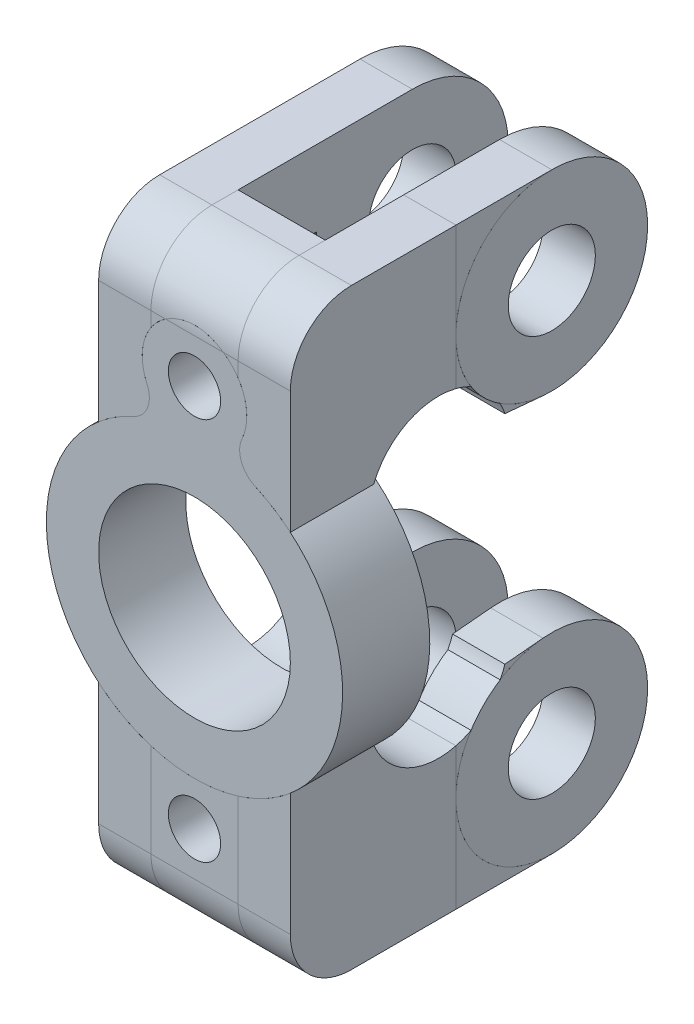
SolidWorks part; units mm, degrees
ref_plane "Front" through (0, 0, 0) normal (0, 0, 1) x (1, 0, 0)
ref_plane "Top" through (0, 0, 0) normal (0, 1, 0) x (1, 0, 0)
ref_plane "Right" through (0, 0, 0) normal (1, 0, 0) x (0, 0, -1)
sketch "Эскиз1" plane through (0, 0, 0) normal (0, 0, 1) x (1, 0, 0)
  line L0 (0, 0) -> (0, 11) construction
  circle A0 centre (0, 0) radius 5.5
  circle A1 centre (0, 0) radius 8.5
  circle A2 centre (0, 11) radius 1.5
  circle A3 centre (0, 11) radius 3
  circle A4 centre (-4.0908, 9.125) radius 1.5
  circle A5 centre (4.0908, 9.125) radius 1.5
  dimension "D1" = 3
  dimension "D2" = 6
  dimension "D3" = 11
  dimension "D4" = 17
  dimension "D5" = 3
  dimension "D6" = 11
extrude "Бобышка-Вытянуть1" add sketch "Эскиз1" along normal blind 5
sketch "Эскиз2" plane through (0, 0, 0) normal (1, 0, 0) x (0, 0, -1)
  line L0 (0, 0) -> (30.7482, 0) construction
  circle A0 centre (10, 11.5) radius 5.5
  circle A1 centre (10, -11.5) radius 5.5
  circle A2 centre (10, 11.5) radius 2.5
  circle A3 centre (10, -11.5) radius 2.5
  dimension "D1" = 11
  dimension "D4" = 5
  dimension "D2" = 10
  dimension "D3" = 23
extrude "Бобышка-Вытянуть2" add sketch "Эскиз2" against normal blind 3 from offset 2.5 separate body offset against normal yes
sketch "Эскиз3" plane through (0, 0, 0) normal (1, 0, 0) x (0, 0, -1)
  line L0 (0, 0) -> (30.7482, 0) construction
  circle A0 centre (10, 11.5) radius 5.5
  circle A1 centre (10, -11.5) radius 5.5
  circle A2 centre (10, 11.5) radius 2.5
  circle A3 centre (10, -11.5) radius 2.5
  circle A4 centre (10, 11.5) radius 5.5 construction
  circle A5 centre (10, -11.5) radius 5.5 construction
extrude "Бобышка-Вытянуть3" add sketch "Эскиз3" along normal blind 3 from offset 2.5 separate body
sketch "Эскиз4" plane through (0, 0, 5) normal (0, 0, 1) x (1, 0, 0)
  line L0 (-5.5, -6.4807) -> (-5.5, -17)
  line L1 (-5.5, -17) -> (-2.5, -17)
  line L2 (-2.5, -17) -> (-2.5, -8.124)
  line L3 (-2.5, -17) -> (-2.5, -6) construction
  line L4 (-5.5, -17) -> (-2.5, -17) construction
  line L5 (-5.5, -6) -> (-5.5, -17) construction
  line L6 (2.5, -8.124) -> (2.5, -17)
  line L7 (2.5, -17) -> (5.5, -17)
  line L8 (5.5, -17) -> (5.5, -6.4807)
  line L9 (-5.5, 6.4807) -> (-5.5, 17)
  line L10 (-5.5, 17) -> (-2.5, 17)
  line L11 (-2.5, 17) -> (-2.5, 12.6583)
  line L12 (-2.5, 6) -> (-2.5, 17) construction
  line L13 (-2.5, 17) -> (-5.5, 17) construction
  line L14 (-5.5, 17) -> (-5.5, 6) construction
  line L15 (5.5, 6.4807) -> (5.5, 17)
  line L16 (5.5, 17) -> (2.5, 17)
  line L17 (2.5, 17) -> (2.5, 12.6583)
  line L18 (2.5, -17) -> (5.5, -17) construction
  line L19 (5.5, -17) -> (5.5, -6) construction
  line L20 (2.5, -6) -> (2.5, -17) construction
  line L21 (5.5, 6) -> (5.5, 17) construction
  line L22 (5.5, 17) -> (2.5, 17) construction
  line L23 (2.5, 17) -> (2.5, 6) construction
  circle A0 centre (0, 0) radius 8.5
  arc A1 (2.7272, 9.75) -> (-2.7272, 9.75) centre (0, 11) ccw construction
  circle A2 centre (0, 11) radius 3
  arc A3 (-3.4772, 7.7563) -> (3.4772, 7.7563) centre (0, 0) ccw construction
  arc M13 (-2.7272, 9.75) -> (-3.4772, 7.7563) centre (-4.0908, 9.125) cw
  arc M14 (-3.4772, 7.7563) -> (3.4772, 7.7563) centre (0, 0) ccw
  arc M15 (3.4772, 7.7563) -> (2.7272, 9.75) centre (4.0908, 9.125) cw
  arc M16 (2.7272, 9.75) -> (-2.7272, 9.75) centre (0, 11) ccw
  dimension "D1" = 17
  dimension "D2" = 6
extrude "Бобышка-Вытянуть4" add sketch "Эскиз4" against normal blind 9.5 separate body contours L1 L2 L0 M14 | L7 L8 L6 M14 | L16 L17 L15 M16 M15 M14 | L11 L10 L9 M14 M13 M16
sketch "Эскиз5" plane through (-5.5, 0, 0) normal (-1, 0, 0) x (0, 0, 1)
  line L0 (-10, 17) -> (-4.5, 17)
  line L1 (-4.5, 17) -> (-4.5, 6.4807)
  line L2 (-4.5, 6.4807) -> (-9.4983, 6.0229)
  line L3 (-9.4983, -6.0229) -> (-4.5, -6.4807)
  line L4 (-4.5, -6.4807) -> (-4.5, -17)
  line L5 (-4.5, -17) -> (-10, -17)
  circle A0 centre (-10, 11.5) radius 5.5 construction
  circle A1 centre (-10, 11.5) radius 5.5
  circle A2 centre (-10, -11.5) radius 5.5 construction
  circle A3 centre (-10, -11.5) radius 5.5
  circle M4 centre (-10, 11.5) radius 5.5
extrude "Бобышка-Вытянуть5" add sketch "Эскиз5" against normal up to surface (3 mm away) contours A3 L4 L3 | A3 L5 L4 | L2 L1 M4 | L1 L0 M4 up to face at (-2.5, 11.5, -12.5)
sketch "Эскиз6" plane through (5.5, 0, 0) normal (1, 0, 0) x (0, 0, -1)
  line L0 (10, 17) -> (4.5, 17)
  line L1 (10, 17) -> (-5, 17) construction
  line L2 (4.5, 17) -> (4.5, 6.4807)
  line L3 (4.5, 6.4807) -> (9.4983, 6.0229)
  line L4 (10, -17) -> (4.5, -17)
  line L5 (4.5, -17) -> (4.5, -6.4807)
  line L6 (4.5, -6.4807) -> (9.4983, -6.0229)
  line L7 (10, -17) -> (-5, -17) construction
  circle A0 centre (10, 11.5) radius 5.5
  circle A1 centre (10, -11.5) radius 5.5
  circle M4 centre (10, 11.5) radius 5.5
  dimension "D1" = 11
  dimension "D2" = 11
extrude "Бобышка-Вытянуть6" add sketch "Эскиз6" against normal up to surface (3 mm away) separate body contours A1 L6 L5 | A1 L5 L4 | L0 L2 M4 | L2 L3 M4 up to face at (2.5, 11.5, -15.5)
sketch "Эскиз7" plane through (0, 0, 5) normal (0, 0, 1) x (1, 0, 0)
  line L0 (-2.5, -8.124) -> (-2.5, -17)
  line L1 (-2.5, -17) -> (2.5, -17)
  line L2 (2.5, -17) -> (2.5, -8.124)
  line L3 (-2.5, 12.6583) -> (-2.5, 17)
  line L4 (-2.5, 17) -> (2.5, 17)
  line L5 (2.5, 17) -> (2.5, 12.6583)
  line L6 (2.5, 17) -> (2.5, 12.6583) construction
  circle A0 centre (0, 0) radius 8.5
  circle A1 centre (0, 11) radius 3
  line M4 (2.5, -8.124) -> (2.5, -17)
  dimension "D1" = 17
  dimension "D2" = 6
extrude "Бобышка-Вытянуть7" add sketch "Эскиз7" against normal blind 5 separate body contours A1 L5 L4 L3 | A0 L0 L1 M4
sketch "Эскиз8" plane through (5.5, 0, 0) normal (1, 0, 0) x (0, 0, -1)
  line L0 (0, 0) -> (22.4841, 0) construction
  line L2 (0, -8.5) -> (0, 7.7563) construction
  circle A0 centre (3.5, 5) radius 4
  circle A1 centre (3.5, -5) radius 4
  point P9 (0, 4.2751)
  dimension "D1" = 8
  dimension "D2" = 5
  dimension "D3" = 3.5
extrude "Вырез-Вытянуть1" cut sketch "Эскиз8" against normal through all
sketch "Эскиз9" plane through (0, 0, 5) normal (0, 0, 1) x (1, 0, 0)
  circle A0 centre (0, -11) radius 1.5
  dimension "D1" = 3
  dimension "D2" = 11
extrude "Вырез-Вытянуть2" cut sketch "Эскиз9" against normal blind 5
sketch "Эскиз10" plane through (5.5, 0, 0) normal (1, 0, 0) x (0, 0, -1)
  line L0 (0, 0) -> (13.6119, 0) construction
  line L1 (4.5, 17) -> (-5, 17) construction
  line L2 (-5, 6.4807) -> (-5, 17) construction
  line L3 (-1.5, 17) -> (-5, 17)
  line L4 (-5, 17) -> (-5, 13.5)
  line L5 (-5, -13.5) -> (-5, -17)
  line L6 (-5, -17) -> (-1.5, -17)
  circle A0 centre (-1.5, -13.5) radius 3.5
  circle A1 centre (-1.5, 13.5) radius 3.5
  line M4 (-5, -6.4807) -> (-5, -17)
  line M5 (-5, -17) -> (4.5, -17)
  dimension "D1" = 7
extrude "Вырез-Вытянуть3" cut sketch "Эскиз10" against normal through all contours A0 M4 M5 | A1 L3 L4
